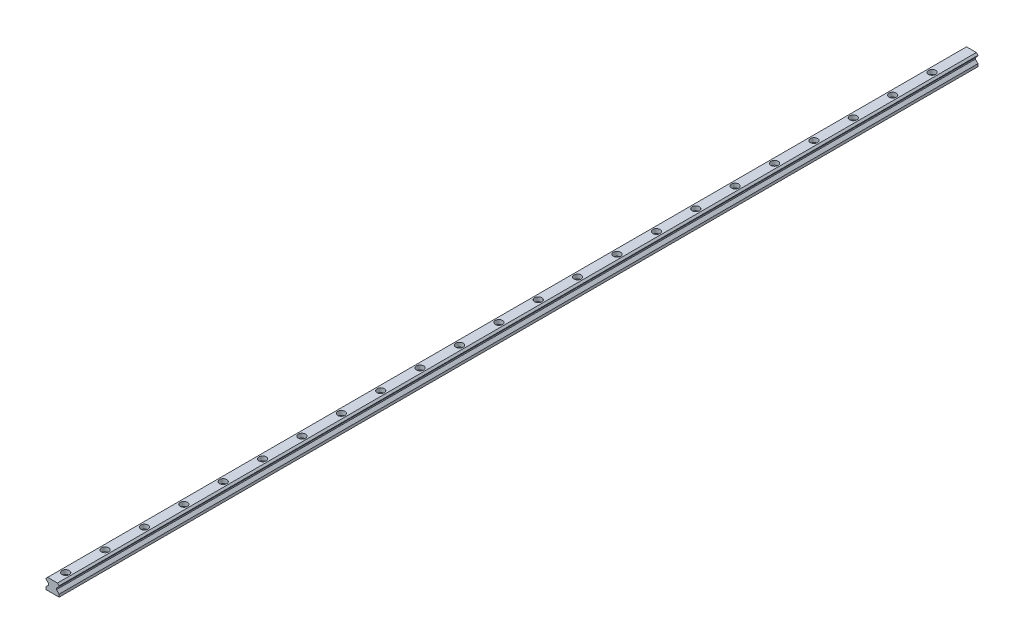
SolidWorks part; units mm, degrees
material "1.4116 (X50CrMoV15)"
ref_plane "Płaszczyzna przednia" through (0, 0, 0) normal (0, 0, 1) x (1, 0, 0)
ref_plane "Płaszczyzna górna" through (0, 0, 0) normal (0, 1, 0) x (1, 0, 0)
ref_plane "Płaszczyzna prawa" through (0, 0, 0) normal (1, 0, 0) x (0, 0, -1)
sketch "Szkic1" plane through (0, 0, 0) normal (0, 0, 1) x (1, 0, 0)
  line L0 (10, 0) -> (-10, 0)
  line L1 (-10, 0) -> (-10, 4)
  line L2 (-10, 4) -> (-6, 8)
  line L3 (-6, 8) -> (-6, 10)
  line L4 (-6, 10) -> (-10, 14)
  line L5 (-10, 14) -> (-10, 15)
  line L6 (-10, 15) -> (-7.5, 17.5)
  line L7 (-7.5, 17.5) -> (0, 17.5)
  line L8 (0, 33.5589) -> (0, -15.4724) construction
  line L9 (7.5, 17.5) -> (0, 17.5)
  line L10 (10, 15) -> (7.5, 17.5)
  line L11 (10, 14) -> (10, 15)
  line L12 (6, 10) -> (10, 14)
  line L13 (6, 8) -> (6, 10)
  line L14 (10, 4) -> (6, 8)
  line L15 (10, 0) -> (10, 4)
  point P12 (-3.75, 17.5)
  point P13 (0, 17.5)
  point P14 (-10.7065, 14.7659)
  point P15 (-9.0109, 15.0485)
  point P16 (-6.4675, 7.5596)
  point P17 (-10, 13.6016)
  point P18 (-6, 9.4272)
  point P19 (-6, 7.3121)
  point P20 (-6, 9)
  point P28 (0, 0)
  dimension "D1" = 20
  dimension "D2" = 45
  dimension "D3" = 45
  dimension "D4" = 17.5
  dimension "D5" = 12
  dimension "D6" = 2
  dimension "D7" = 1
  dimension "D8" = 8.5
extrude "Dodanie-wyciągnięcie1" add sketch "Szkic1" along normal blind 1400
sketch "Szkic2" plane through (0, 17.5, 0) normal (0, 1, 0) x (1, 0, 0)
  line L0 (7.5, -1400) -> (-7.5, -1400) construction
  circle A0 centre (0, -1380) radius 4
  point P4 (0, 0)
  point P5 (0, -1400)
  dimension "D2" = 8
  dimension "D1" = 20
hole_wizard "Pogłębienie walcowe pod M6 Wkręt z łbem walcowym z gniazdem sześciokątnym1" positions "Szkic7" profile "Szkic6" counterbore size "M6" standard "ISO" end condition through all
sketch "Szkic7" plane through (0, 17.5, 0) normal (0, 1, 0) x (1, 0, 0)
  point P0 (0, -1380)
sketch "Szkic6" plane through (0, 17.5, 1380) normal (1, 0, 0) x (0, 0, 1)
  line L0 (0, 0) -> (0, 17.5)
  line L1 (0, 17.5) -> (3.3, 17.5)
  line L3 (3.3, 17.5) -> (3.3, 6.4)
  line L4 (3.3, 6.4) -> (5.5, 6.4)
  line L5 (5.5, 6.4) -> (5.5, 0)
  line L7 (5.5, 0) -> (0, 0)
  line L11 (0, -6.35) -> (0, 107.95) construction
  dimension "Średnica otworu na wylot" = 6.6
  dimension "Głębokość otworu na wylot" = 17.5
  dimension "Średnica pogłębienia walcowego" = 11
  dimension "Głębokość pogłębienia walcowego" = 6.4
pattern_linear "Szyk liniowy1" count 23 spacing 60 along (0, 0, -1) of "Pogłębienie walcowe pod M6 Wkręt z łbem walcowym z gniazdem sześciokątnym1"
